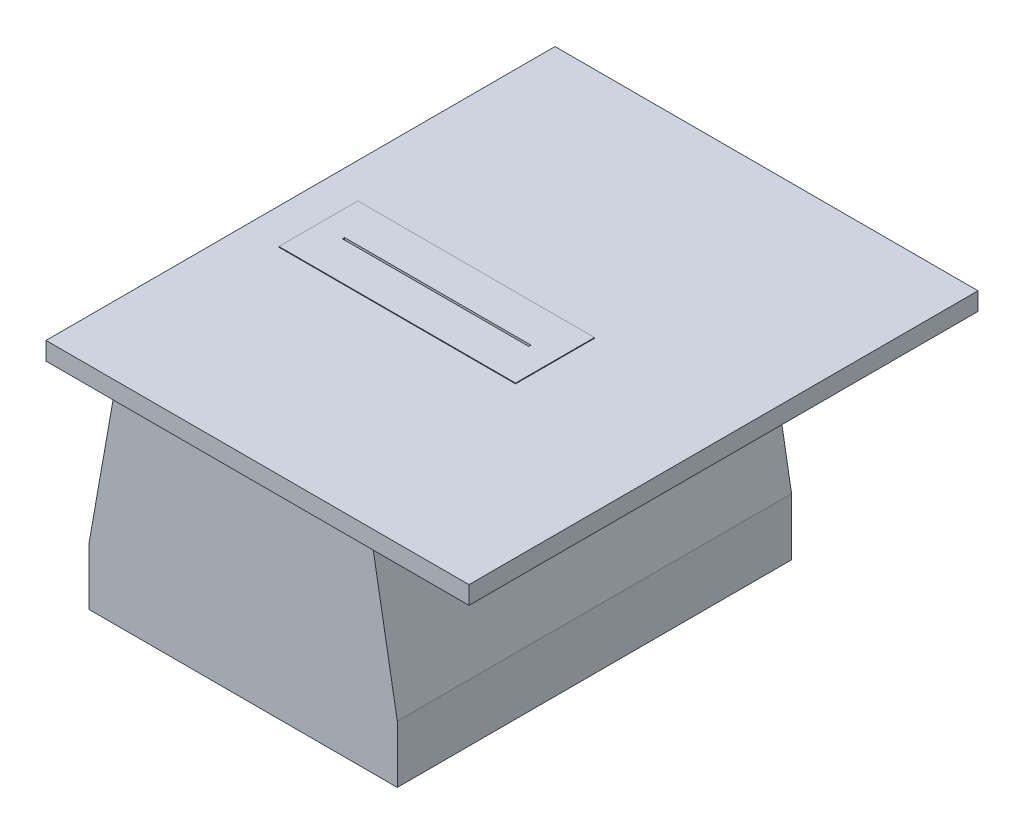
SolidWorks part; units mm, degrees
ref_plane "Plan de face" through (0, 0, 0) normal (0, 0, 1) x (1, 0, 0)
ref_plane "Plan de dessus" through (0, 0, 0) normal (0, 1, 0) x (1, 0, 0)
ref_plane "Plan de droite" through (0, 0, 0) normal (1, 0, 0) x (0, 0, -1)
sketch "Esquisse1" plane through (0, 0, 0) normal (0, 0, 1) x (1, 0, 0)
  line L0 (-215, 0) -> (215, 0)
  line L1 (215, 0) -> (215, 80)
  line L2 (215, 80) -> (176.2081, 300)
  line L3 (176.2081, 300) -> (-176.2081, 300)
  line L4 (0, 300) -> (0, 0) construction
  line L5 (-215, 80) -> (-176.2081, 300)
  line L6 (-215, 0) -> (-215, 80)
  dimension "D1" = 300
  dimension "D2" = 430
  dimension "D3" = 170
  dimension "D4" = 80
extrude "Boss.-Extru.1" add sketch "Esquisse1" along normal blind 550
sketch "Esquisse2" plane through (0, 300, 0) normal (0, 1, 0) x (1, 0, 0)
  line L0 (0, -550) -> (0, 0) construction
  line L1 (176.2081, -550) -> (-176.2081, -550) construction
  line L3 (-245, 130) -> (345, 130)
  line L4 (-245, 130) -> (-245, -580)
  line L5 (-245, -580) -> (345, -580)
  line L6 (345, 130) -> (345, -580)
  line L7 (176.2081, 0) -> (-176.2081, 0) construction
  line L8 (215, -550) -> (215, 0) construction
  point P5 (0, -275)
  dimension "D1" = 710
  dimension "D2" = 590
  dimension "D3" = 130
  dimension "D4" = 130
extrude "Boss.-Extru.2" add sketch "Esquisse2" along normal blind 25
sketch "Esquisse3" plane through (0, 325, 0) normal (0, 1, 0) x (1, 0, 0)
  line L0 (-245, -580) -> (345, -580) construction
  line L1 (-195, -195) -> (135, -195)
  line L2 (-195, -195) -> (-195, -305)
  line L3 (-195, -305) -> (135, -305)
  line L4 (135, -195) -> (135, -305)
  line L5 (-245, 130) -> (-245, -580) construction
  dimension "D1" = 330
  dimension "D2" = 275
  dimension "D3" = 50
  dimension "D4" = 110
extrude "Boss.-Extru.3" add sketch "Esquisse3" along normal blind 1
sketch "Esquisse4" plane through (0, 326, 0) normal (0, 1, 0) x (1, 0, 0)
  line L0 (-160, -250) -> (-195, -250) construction
  line L1 (-160, -248.5) -> (100, -248.5)
  line L2 (-160, -248.5) -> (-160, -251.5)
  line L3 (-160, -251.5) -> (100, -251.5)
  line L4 (100, -248.5) -> (100, -251.5)
  line L5 (-195, -195) -> (-195, -305) construction
  line L6 (-30, -251.5) -> (-30, -305) construction
  line L7 (-195, -305) -> (135, -305) construction
  dimension "D1" = 3
  dimension "D2" = 260
extrude "Enlèv. mat.-Extru.1" cut sketch "Esquisse4" against normal blind 3
